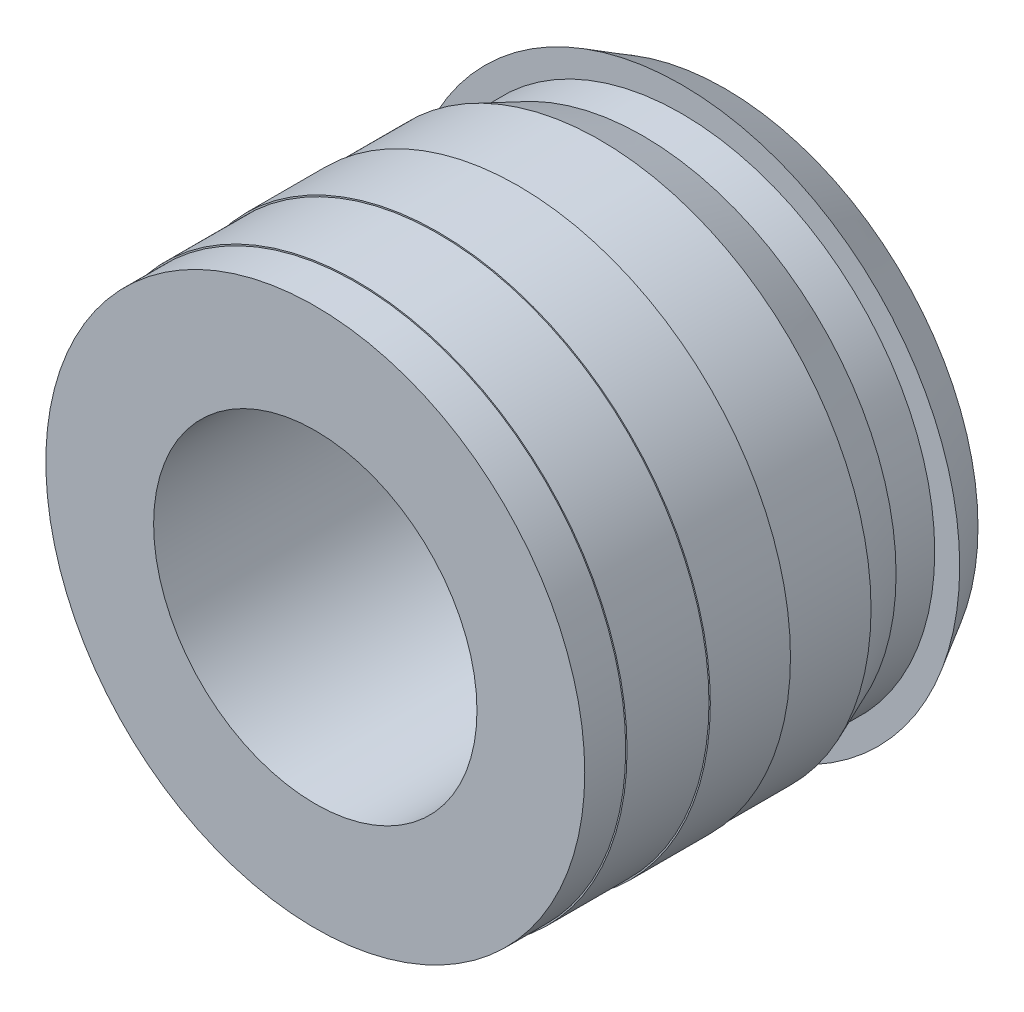
SolidWorks part; units mm, degrees
material "Brass"
ref_plane "Front Plane" through (0, 0, 0) normal (0, 0, 1) x (1, 0, 0)
ref_plane "Top Plane" through (0, 0, 0) normal (0, 1, 0) x (1, 0, 0)
ref_plane "Right Plane" through (0, 0, 0) normal (1, 0, 0) x (0, 0, -1)
sketch "Sketch1" plane through (0, 0, 0) normal (1, 0, 0) x (0, 0, -1)
  line L0 (-1.9, 0) -> (1.9, 0) construction
  line L1 (-1.9, 1.5) -> (-1.9, 2.5)
  line L2 (-1.9, 2.5) -> (-1.52, 2.5)
  line L3 (-1.52, 2.5) -> (-1.52, 2.5125)
  line L4 (-1.52, 2.5125) -> (-0.76, 2.5125)
  line L5 (-0.76, 2.5125) -> (-0.76, 2.525)
  line L6 (-0.76, 2.525) -> (-0.0165, 2.525)
  line L7 (-0.0165, 2.525) -> (-0.0165, 2.5125)
  line L9 (0.7435, 2.5125) -> (1.14, 2.3482)
  line L13 (1.14, 2.3482) -> (1.4986, 2.3482)
  line L14 (1.4986, 2.3482) -> (1.4986, 2.58)
  line L15 (1.4986, 2.58) -> (1.9, 2.3482)
  line L16 (1.9, 2.3482) -> (1.9, 1.5)
  line L17 (-1.9, 2.58) -> (1.9, 2.58) construction
  line L18 (1.9, 0) -> (1.9, 2.58) construction
  line L19 (-1.9, 0) -> (-1.9, 2.5) construction
  line L20 (-0.0165, 2.5125) -> (0.7435, 2.5125)
  line L21 (-1.9, 1.5) -> (1.9, 1.5)
  line L23 (-2.3688, 1.5541) -> (-2.1187, 1.1211) construction
  line L24 (-1.9, -2.58) -> (1.9, -2.58) construction
  line L25 (-2.1187, 1.1211) -> (-1.8687, 1.5541) construction
  line L26 (-1.8687, 1.5541) -> (-2.3688, 1.5541) construction
  line L27 (-2.3375, 1.5) -> (-1.9, 1.5) construction
  line L28 (-2.1187, 1.5541) -> (-2.1187, 1.5) construction
  line L29 (-2.1187, 1.5) -> (-2.1187, 1.1752) construction
  line L30 (-2.1187, 1.1752) -> (-2.1187, 1.1211) construction
  line L31 (-2.15, 1.1752) -> (-2.0875, 1.1752)
  line L32 (-2.3531, 1.5271) -> (-1.8844, 1.5271)
  line L33 (-2.0875, 1.1752) -> (-1.8844, 1.5271)
  line L34 (-2.15, 1.1752) -> (-2.3531, 1.5271)
  line L35 (-1.9, 2.525) -> (1.9, 2.525) construction
  line L36 (-1.9, -2.525) -> (1.9, -2.525) construction
  point P36 (-2.1187, 1.5271)
  dimension "Installed Length" = 3.8
  dimension "Dia A" = 5
  dimension "Dia B" = 5.16
  dimension "Thread Dia" = 3
  dimension "D6" = 30
  dimension "D8" = 0.76
  dimension "D4" = 22.5
  dimension "Thread Pitch" = 0.5
  dimension "D2" = 0.0625
  dimension "Max Hole Dia" = 5.05
  dimension "Knurling Length" = 2.66
  dimension "D1" = 4.6965
  dimension "D3" = 0.38
ref_plane "Plane1" through (0, 0, 1.52) normal (0, 0, 1) x (1, 0, 0)
sketch "Sketch2" plane through (0, 0, 1.52) normal (0, 0, 1) x (1, 0, 0)
  line L0 (0, 0) -> (0, 2.5125) construction
  line L1 (-0.5059, 2.4713) -> (0, 2.525)
  line L2 (0.5059, 2.4713) -> (0, 2.525)
  line L3 (-0.1753, 2.5064) -> (0, 0) construction
  line L4 (0.1753, 2.5064) -> (0, 0) construction
  line L5 (0, 0) -> (-0.3279, 2.491) construction
  line L6 (0, 0) -> (0.3279, 2.491) construction
  line L7 (0, 0) -> (1.7766, 1.7766) construction
  line L8 (0, 0) -> (0, -1.5541) construction
  line L9 (0, 0) -> (0.7771, -1.3459) construction
  circle A0 centre (0, 0) radius 2.525 construction
  circle A1 centre (0, 0) radius 2.5125 construction
  circle A3 centre (0, 0) radius 1.5541
  arc A4 (-0.5059, 2.4713) -> (0.5059, 2.4713) centre (0, 0) cw
  dimension "D2" = 0.01
  dimension "D1" = 30
  dimension "Knurl Angle" = 8
  dimension "Pattern Angle" = 15
  dimension "Helix Angle" = 45
sketch "Sketch3" plane through (0, 0, 0) normal (1, 0, 0) x (0, 0, -1)
  line L0 (-1.9, 1.5) -> (-1.9, 2.5) construction
  line L1 (-1.9, 2.5) -> (-1.52, 2.5) construction
  line L2 (-1.52, 2.5) -> (-1.52, 2.5125) construction
  line L3 (-1.52, 2.5125) -> (-0.76, 2.5125) construction
  line L4 (-0.76, 2.5125) -> (-0.76, 2.525) construction
  line L5 (-0.76, 2.525) -> (-0.0165, 2.525) construction
  line L6 (-0.0165, 2.525) -> (-0.0165, 2.5125) construction
  line L8 (0.7435, 2.5125) -> (1.14, 2.3482) construction
  line L12 (1.14, 2.3482) -> (1.4986, 2.3482) construction
  line L13 (1.4986, 2.3482) -> (1.4986, 2.58) construction
  line L14 (1.4986, 2.58) -> (1.9, 2.3482) construction
  line L15 (1.9, 2.3482) -> (1.9, 1.5) construction
  line L16 (-1.9, 1.5) -> (1.9, 1.5) construction
  line L17 (-1.9, 1.5) -> (-1.9, 2.5)
  line L18 (-1.9, 2.5) -> (-1.52, 2.5)
  line L19 (-1.52, 2.5) -> (-1.52, 2.5125)
  line L20 (-1.52, 2.5125) -> (-0.76, 2.5125)
  line L21 (-0.76, 2.5125) -> (-0.76, 2.525)
  line L22 (-0.76, 2.525) -> (-0.0165, 2.525)
  line L23 (-0.0165, 2.525) -> (-0.0165, 2.5125)
  line L25 (0.7435, 2.5125) -> (1.14, 2.3482)
  line L29 (1.14, 2.3482) -> (1.4986, 2.3482)
  line L30 (1.4986, 2.3482) -> (1.4986, 2.58)
  line L31 (1.4986, 2.58) -> (1.9, 2.3482)
  line L32 (1.9, 2.3482) -> (1.9, 1.5)
  line L33 (-1.9, 1.5) -> (1.9, 1.5)
  line L34 (-0.0165, 2.5125) -> (0.7435, 2.5125) construction
  line L35 (-0.0165, 2.5125) -> (0.7435, 2.5125)
revolve "Revolve1" add sketch "Sketch3" angle 360 about L0
equation "\"D8@Sketch1\"=\"Installed Length@Sketch1\" * .2"
equation "\"D2@Sketch1\" = \"Thread Pitch@Sketch1\" / 8"
equation "\"Knurling Length@Sketch1\"=\"Installed Length@Sketch1\" * .7"
equation "\"D1@Sketch1\"=\"Max Hole Dia@Sketch1\"*.93"
equation "\"D3@Sketch1\"=\"Installed Length@Sketch1\"*.1"
